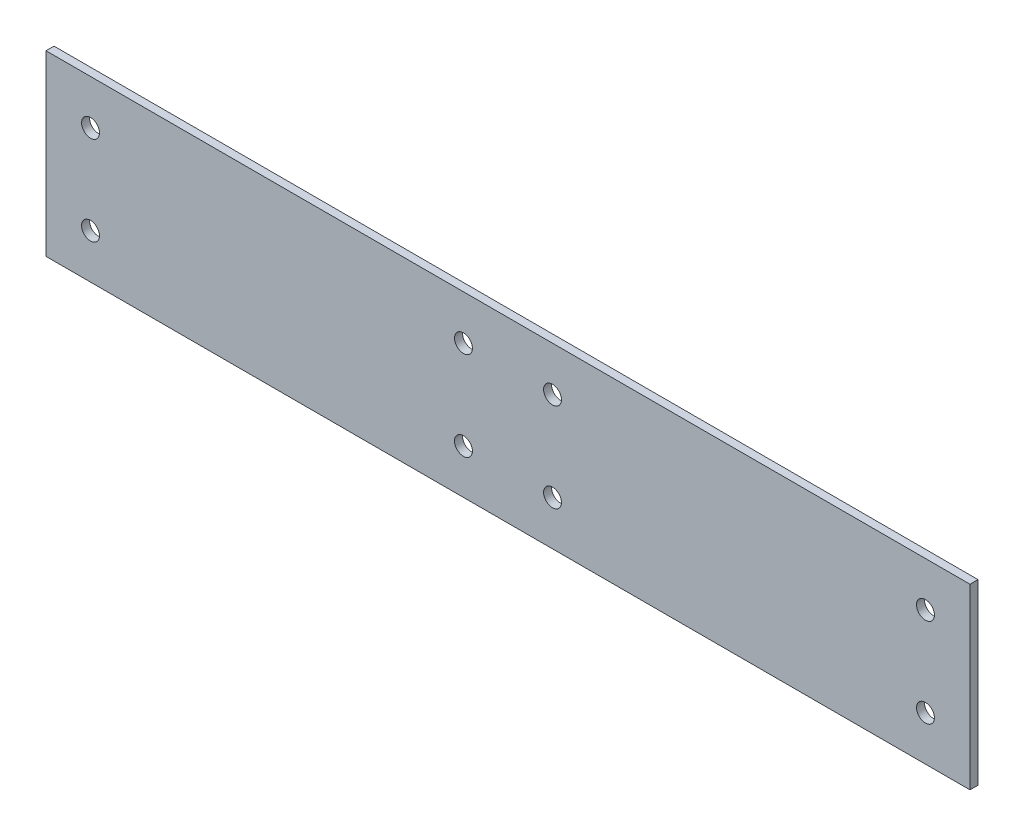
SolidWorks part; units mm, degrees
ref_plane "Front Plane" through (0, 0, 0) normal (0, 0, 1) x (1, 0, 0)
ref_plane "Top Plane" through (0, 0, 0) normal (0, 1, 0) x (1, 0, 0)
ref_plane "Right Plane" through (0, 0, 0) normal (1, 0, 0) x (0, 0, -1)
sketch "Sketch1" plane through (0, 0, 0) normal (0, 0, 1) x (1, 0, 0)
  line L0 (-131.7625, 25.4) -> (-131.7625, -25.4)
  line L1 (-131.7625, -25.4) -> (131.7625, -25.4)
  line L2 (131.7625, -25.4) -> (131.7625, 25.4)
  line L3 (131.7625, 25.4) -> (-131.7625, 25.4)
  line L4 (0, 0) -> (0, -152.4) construction
  line L5 (-25.4, 0) -> (-25.4, -152.4) construction
  line L6 (25.4, 0) -> (25.4, -152.4) construction
  line L7 (-25.4, 0) -> (25.4, 0) construction
  line L8 (-25.4, -152.4) -> (25.4, -152.4) construction
  point P4 (0, -25.4)
  point P5 (-131.7625, 0)
  dimension "D1" = 50.8
  dimension "D2" = 263.525
  dimension "D3" = 152.4
  dimension "D4" = 25.4
  dimension "D5" = 25.4
extrude "Boss-Extrude1" add sketch "Sketch1" along normal mid plane 2.286 contours L5 L7 L6 L1 L2 L3 L0 | L4 L7 L5 L1 | L7 L4 L1 L6 | L1 L4 L8 L6 | L4 L1 L5 L8
hole_wizard "#10 Clearance Hole1" positions "Sketch3" profile "Sketch2" hole size "#10" standard "ANSI Inch" end condition through all
sketch "Sketch3" plane through (0, 0, 1.143) normal (0, 0, 1) x (1, 0, 0)
  line L0 (-131.7625, 25.4) -> (-131.7625, -25.4) construction
  line L1 (131.7625, 25.4) -> (-131.7625, 25.4) construction
  line L2 (-131.7625, -25.4) -> (131.7625, -25.4) construction
  line L4 (-12.7, -12.7) -> (12.7, -12.7) construction
  line L5 (-12.7, -12.7) -> (-12.7, 12.7) construction
  line L6 (-12.7, 12.7) -> (12.7, 12.7) construction
  line L7 (12.7, -12.7) -> (12.7, 12.7) construction
  line L8 (-12.7, -12.7) -> (12.7, 12.7) construction
  line L9 (-12.7, 12.7) -> (12.7, -12.7) construction
  line L11 (0, -60.3453) -> (0, 57.9969) construction
  point P0 (-119.0625, 12.7)
  point P25 (-119.0625, -12.7)
  point P30 (-12.7, 12.7)
  point P32 (-12.7, -12.7)
  point P34 (12.7, -12.7)
  point P36 (12.7, 12.7)
  point P70 (0, 0)
  point P78 (119.0625, 12.7)
  point P79 (119.0625, -12.7)
  dimension "D5" = 25.4
  dimension "D1" = 12.7
  dimension "D2" = 12.7
  dimension "D4" = 12.7
  dimension "D6" = 12.7
  dimension "D7" = 25.4
  dimension "D3" = 2
sketch "Sketch2" plane through (-119.0625, 12.7, 1.143) normal (1, 0, 0) x (0, -1, 0)
  line L0 (0, 0) -> (0, 2.286)
  line L1 (0, 2.286) -> (2.5527, 2.286)
  line L2 (2.5527, 2.286) -> (2.5527, 0)
  line L5 (2.5527, 0) -> (0, 0)
  line L11 (0, -6.35) -> (0, 107.95) construction
  dimension "Thru Hole Dia." = 5.1054
  dimension "Thru Hole Depth" = 2.286
